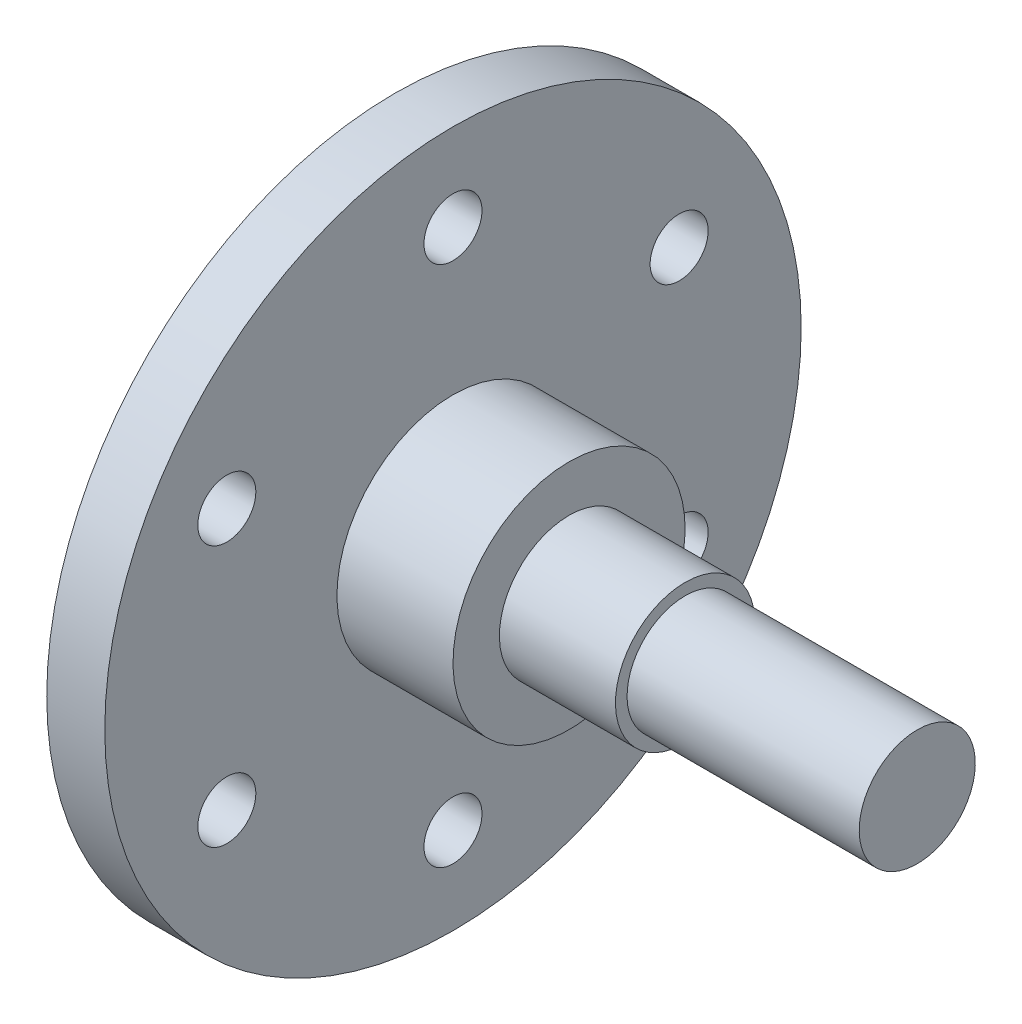
SolidWorks part; units mm, degrees
ref_plane "前视基准面" through (0, 0, 0) normal (0, 0, 1) x (1, 0, 0)
ref_plane "上视基准面" through (0, 0, 0) normal (0, 1, 0) x (1, 0, 0)
ref_plane "右视基准面" through (0, 0, 0) normal (1, 0, 0) x (0, 0, -1)
sketch "草图1" plane through (0, 0, 0) normal (0, 0, 1) x (1, 0, 0)
  line L0 (0, -30) -> (0, 30)
  line L1 (0, 30) -> (5, 30)
  line L2 (5, 30) -> (5, 10)
  line L3 (5, 10) -> (15, 10)
  line L4 (15, 10) -> (15, 6)
  line L5 (15, 6) -> (25, 6)
  line L6 (25, 6) -> (25, 5)
  line L7 (25, 5) -> (45, 5)
  line L8 (45, 5) -> (45, -5)
  line L9 (45, 0) -> (0, 0) construction
  line L10 (25, -5) -> (45, -5)
  line L11 (25, -6) -> (25, -5)
  line L12 (15, -6) -> (25, -6)
  line L13 (15, -10) -> (15, -6)
  line L14 (5, -10) -> (15, -10)
  line L15 (5, -30) -> (5, -10)
  line L16 (0, -30) -> (5, -30)
  dimension "D1" = 60
  dimension "D2" = 20
  dimension "D3" = 12
  dimension "D4" = 10
  dimension "D5" = 5
  dimension "D6" = 10
  dimension "D7" = 10
  dimension "D8" = 20
revolve "旋转2" add sketch "草图1" angle 360 about L9
sketch "草图2" plane through (0, 0, 0) normal (-1, 0, 0) x (0, 0, 1)
  line L0 (0, 0) -> (0, 30) construction
  line L1 (0, 0) -> (0, 22.5) construction
  line L2 (0, 0) -> (19.4856, 11.25) construction
  circle A0 centre (0, 0) radius 30 construction
  circle A1 centre (0, 22.5) radius 2.5
  circle A2 centre (19.4856, 11.25) radius 2.5
  circle A3 centre (19.4856, -11.25) radius 2.5
  circle A4 centre (0, -22.5) radius 2.5
  circle A5 centre (-19.4856, -11.25) radius 2.5
  circle A6 centre (-19.4856, 11.25) radius 2.5
  dimension "D3" = 45
  dimension "D4" = 5
  dimension "D2" = 60
  dimension "D1" = 6
extrude "切除-拉伸1" cut sketch "草图2" against normal through all
